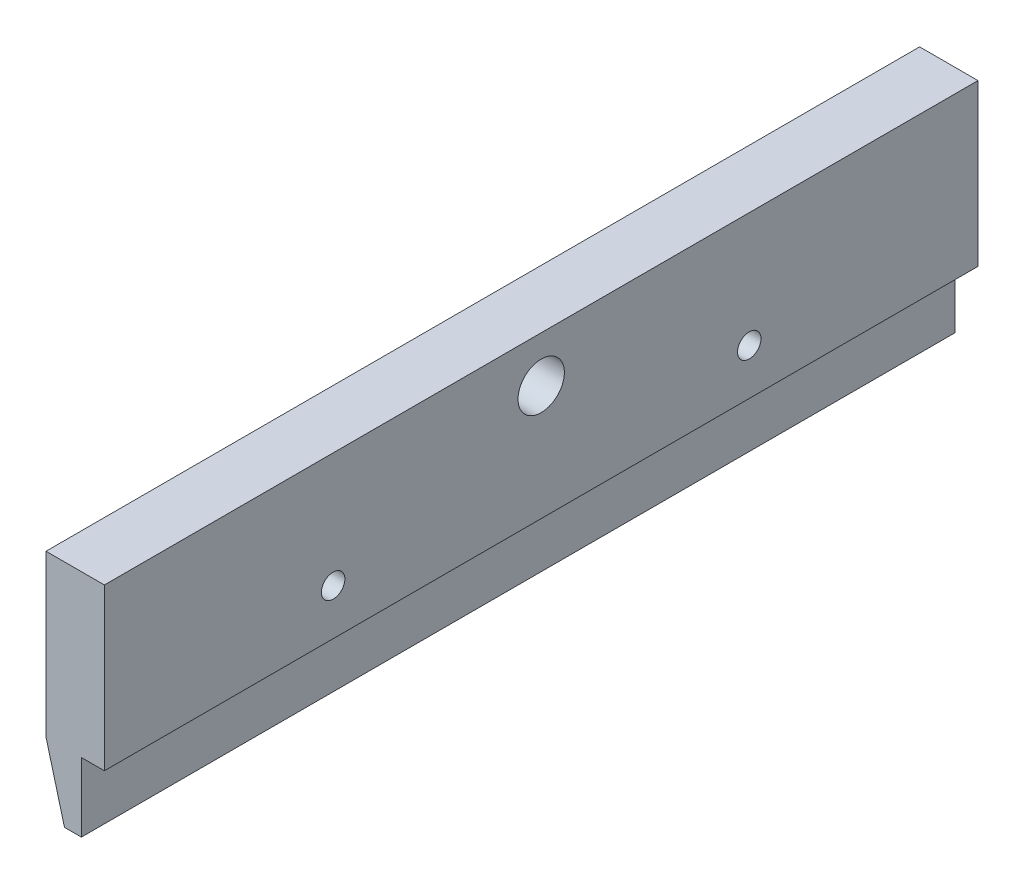
SolidWorks part; units mm, degrees
ref_plane "Alzado" through (0, 0, 0) normal (0, 0, 1) x (1, 0, 0)
ref_plane "Planta" through (0, 0, 0) normal (0, 1, 0) x (1, 0, 0)
ref_plane "Vista lateral" through (0, 0, 0) normal (1, 0, 0) x (0, 0, -1)
sketch "Croquis1" plane through (0, 0, 0) normal (0, 0, 1) x (1, 0, 0)
  line L0 (6.35, -17.5) -> (1.35, -17.5)
  line L1 (-6.35, 17.5) -> (6.35, 17.5)
  line L2 (-6.35, 17.5) -> (-6.35, -17.5)
  line L3 (-2.3308, -32.5) -> (1.35, -32.5)
  line L4 (6.35, 17.5) -> (6.35, -17.5)
  line L5 (1.35, -17.5) -> (1.35, -32.5)
  line L6 (-2.3308, -32.5) -> (-6.35, -17.5)
  point P1 (0, 17.5)
  point P6 (-6.35, 0)
  dimension "D1" = 12.7
  dimension "D2" = 50
  dimension "D3" = 15
  dimension "D4" = 5
  dimension "D6" = 15
extrude "Saliente-Extruir1" add sketch "Croquis1" along normal mid plane 190
hole_wizard "Taladro roscado 1/4-201" positions "Croquis2" profile "Croquis3" tap size "1/4-20" standard "Ansi Inch" end condition through all
sketch "Croquis2" plane through (6.35, 0, 0) normal (1, 0, 0) x (0, 0, -1)
  point P3 (45.25, -7.5)
  point P6 (-45.25, -7.5)
sketch "Croquis3" plane through (6.35, -7.5, -45.25) normal (0, 1, 0) x (0, 0, -1)
  line L0 (0, 0) -> (0, 12.7)
  line L1 (0, 12.7) -> (2.5527, 12.7)
  line L2 (2.5527, 12.7) -> (2.5527, 0)
  line L5 (2.5527, 0) -> (0, 0)
  line L11 (0, -6.35) -> (0, 107.95) construction
  dimension "Diámetro de perforador para roscar hasta el siguiente" = 5.1054
  dimension "Profundidad de perforador para roscar hasta el siguiente" = 12.7
cosmetic thread "Rosca de taladro1" parameters "D1"=12.7, "D2"=6.35
cosmetic thread "Rosca de taladro2" parameters "D1"=12.7, "D2"=6.35
hole_wizard "Taladro de margen para 3/81" positions "Croquis4" profile "Croquis5" hole size "3/8" standard "Ansi Inch" end condition through all
sketch "Croquis4" plane through (6.35, 0, 0) normal (1, 0, 0) x (0, 0, -1)
  point P0 (0, 7.5)
  dimension "D1" = 10
sketch "Croquis5" plane through (6.35, 7.5, 0) normal (0, 1, 0) x (0, 0, -1)
  line L0 (0, 0) -> (0, 12.7)
  line L1 (0, 12.7) -> (5.0419, 12.7)
  line L2 (5.0419, 12.7) -> (5.0419, 0)
  line L5 (5.0419, 0) -> (0, 0)
  line L11 (0, -6.35) -> (0, 107.95) construction
  dimension "Diámetro de taladro hasta el siguiente" = 10.0838
  dimension "Profundidad de taladro hasta el siguiente" = 12.7
